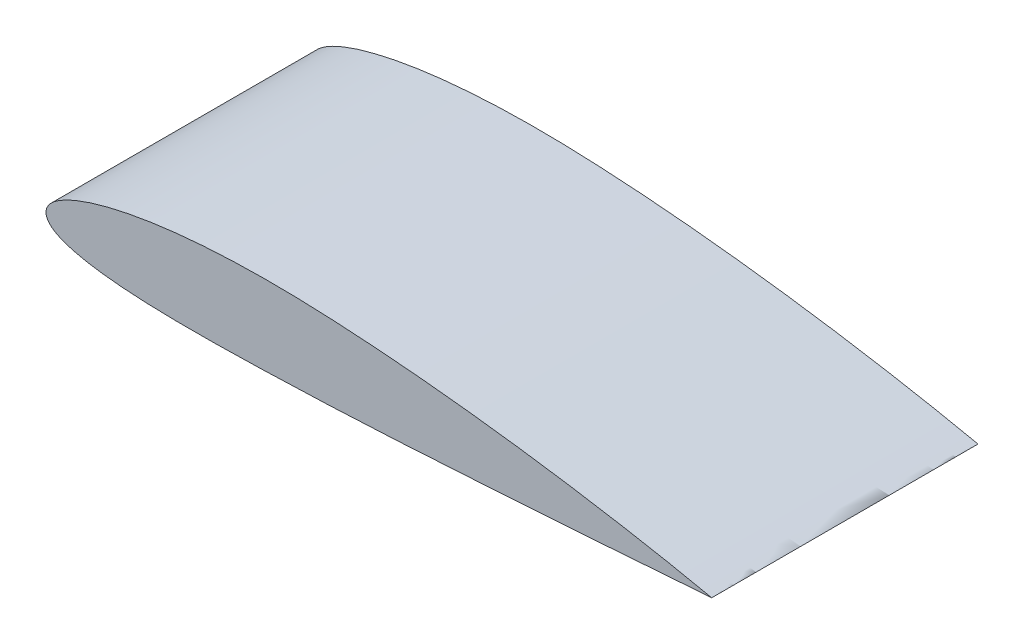
SolidWorks part; units mm, degrees
ref_plane "Front Plane"
ref_plane "Top Plane" through (0, 0, 0) normal (0, 1, 0) x (1, 0, 0)
ref_plane "Right Plane" through (0, 0, 0) normal (1, 0, 0) x (0, 0, -1)
curve "Curve2"
  spline degree 3 poles (749.6002, -0.0183, 0) (750.0992, -0.0066, 0) (749.6062, 0.0712, 0) (749.2018, 0.1788, 0) (748.204, 0.3795, 0) (746.9606, 0.6495, 0) (745.3027, 0.9992, 0) (743.302, 1.423, 0) (740.9341, 1.9213, 0) (738.2104, 2.492, 0) (735.1303, 3.1336, 0) (731.6977, 3.8441, 0) (727.9155, 4.6215, 0) (723.7872, 5.4635, 0) (719.3167, 6.3677, 0) (714.5081, 7.3314, 0) (709.366, 8.352, 0) (703.8952, 9.4265, 0) (698.1007, 10.5521, 0) (691.988, 11.7256, 0) (685.563, 12.9439, 0) (678.8316, 14.2037, 0) (671.8002, 15.5017, 0) (664.4756, 16.8346, 0) (656.8646, 18.1989, 0) (648.9745, 19.5912, 0) (640.8129, 21.008, 0) (632.3875, 22.4457, 0) (623.7065, 23.9009, 0) (614.7782, 25.3701, 0) (605.6111, 26.8497, 0) (596.2141, 28.3363, 0) (586.5964, 29.8262, 0) (576.7671, 31.316, 0) (566.7359, 32.8022, 0) (556.5125, 34.2813, 0) (546.1069, 35.7499, 0) (535.5292, 37.2046, 0) (524.7898, 38.6418, 0) (513.8991, 40.0583, 0) (502.8679, 41.4506, 0) (491.707, 42.8155, 0) (480.4274, 44.1495, 0) (469.0403, 45.4494, 0) (457.5568, 46.7119, 0) (445.9883, 47.9338, 0) (434.3464, 49.1119, 0) (422.6425, 50.2431, 0) (410.8883, 51.3242, 0) (399.0956, 52.3523, 0) (387.2762, 53.3242, 0) (375.4418, 54.2373, 0) (363.6043, 55.0885, 0) (351.7755, 55.8752, 0) (339.9675, 56.5947, 0) (328.1921, 57.2446, 0) (316.4612, 57.8222, 0) (304.7683, 58.3269, 0) (293.1124, 58.7536, 0) (281.5044, 59.0737, 0) (269.9749, 59.2908, 0) (258.5487, 59.4022, 0) (247.2379, 59.4077, 0) (236.0543, 59.3068, 0) (225.0098, 59.0996, 0) (214.1161, 58.7862, 0) (203.3848, 58.3674, 0) (192.8272, 57.8441, 0) (182.4546, 57.2175, 0) (172.2778, 56.4892, 0) (162.3077, 55.6611, 0) (152.5548, 54.7354, 0) (143.0294, 53.7146, 0) (133.7414, 52.6014, 0) (124.7005, 51.3989, 0) (115.9163, 50.1105, 0) (107.3977, 48.7396, 0) (99.1536, 47.2902, 0) (91.1924, 45.7662, 0) (83.5221, 44.1717, 0) (76.1506, 42.5112, 0) (69.0852, 40.7891, 0) (62.3329, 39.0099, 0) (55.9002, 37.1784, 0) (49.7935, 35.2991, 0) (44.0185, 33.3768, 0) (38.5806, 31.4161, 0) (33.4849, 29.4217, 0) (28.7359, 27.398, 0) (24.3378, 25.3495, 0) (20.2944, 23.2803, 0) (16.6088, 21.1944, 0) (13.2841, 19.0955, 0) (10.3224, 16.9868, 0) (7.7258, 14.8713, 0) (5.4959, 12.7512, 0) (3.634, 10.6277, 0) (2.1419, 8.5017, 0) (1.022, 6.3729, 0) (0.2783, 4.2417, 0) (-0.0843, 2.1103, 0) (-0.0622, -0.0062, 0) (0.3352, -2.0851, 0) (1.1109, -4.1024, 0) (2.257, -6.0449, 0) (3.7669, -7.9123, 0) (5.6355, -9.7063, 0) (7.8594, -11.4286, 0) (10.4356, -13.0806, 0) (13.3615, -14.6629, 0) (16.6342, -16.1757, 0) (20.2506, -17.6189, 0) (24.2069, -18.9922, 0) (28.499, -20.2953, 0) (33.1227, -21.5276, 0) (38.0731, -22.6889, 0) (43.3451, -23.7788, 0) (48.9333, -24.7972, 0) (54.832, -25.744, 0) (61.0352, -26.6192, 0) (67.5369, -27.423, 0) (74.3304, -28.1556, 0) (81.4091, -28.8177, 0) (88.7662, -29.4098, 0) (96.3944, -29.9328, 0) (104.2864, -30.3876, 0) (112.4348, -30.7756, 0) (120.8318, -31.098, 0) (129.4695, -31.3566, 0) (138.3398, -31.553, 0) (147.4345, -31.6892, 0) (156.7452, -31.7674, 0) (166.2632, -31.79, 0) (175.98, -31.7594, 0) (185.8864, -31.6782, 0) (195.9736, -31.5494, 0) (206.2322, -31.3757, 0) (216.653, -31.1602, 0) (227.2264, -30.9061, 0) (237.9428, -30.6166, 0) (248.7924, -30.2949, 0) (259.7654, -29.9444, 0) (270.8516, -29.5683, 0) (282.041, -29.1703, 0) (293.3358, -28.7518, 0) (304.7441, -28.3213, 0) (316.2539, -27.8553, 0) (327.8413, -27.354, 0) (339.477, -26.8216, 0) (351.1497, -26.2606, 0) (362.8482, -25.6738, 0) (374.5611, -25.0637, 0) (386.277, -24.4329, 0) (397.9847, -23.7839, 0) (409.6726, -23.1191, 0) (421.3295, -22.4407, 0) (432.9439, -21.7512, 0) (444.5044, -21.0525, 0) (455.9998, -20.3466, 0) (467.4187, -19.6356, 0) (478.75, -18.9211, 0) (489.9824, -18.2049, 0) (501.1048, -17.4886, 0) (512.1063, -16.7737, 0) (522.976, -16.0616, 0) (533.703, -15.3535, 0) (544.2767, -14.6508, 0) (554.6866, -13.9546, 0) (564.9222, -13.2658, 0) (574.9734, -12.5856, 0) (584.8301, -11.9149, 0) (594.4823, -11.2546, 0) (603.9204, -10.6056, 0) (613.1349, -9.9687, 0) (622.1165, -9.3446, 0) (630.8561, -8.7342, 0) (639.3449, -8.1383, 0) (647.5742, -7.5575, 0) (655.5356, -6.9926, 0) (663.2211, -6.4444, 0) (670.6228, -5.9136, 0) (677.7332, -5.4009, 0) (684.545, -4.907, 0) (691.0511, -4.4328, 0) (697.2448, -3.9789, 0) (703.1199, -3.5461, 0) (708.6702, -3.135, 0) (713.8899, -2.7465, 0) (718.7737, -2.3812, 0) (723.3165, -2.0397, 0) (727.5136, -1.7229, 0) (731.3606, -1.4312, 0) (734.8534, -1.1653, 0) (737.9886, -0.9258, 0) (740.7621, -0.7131, 0) (743.1739, -0.5279, 0) (745.2124, -0.37, 0) (746.9016, -0.2416, 0) (748.1697, -0.1382, 0) (749.1851, -0.0714, 0) (749.6002, -0.0183, 0) (750.0992, -0.0066, 0) (749.6062, 0.0712, 0) knots -0.001101 -0.000489 -0.000122 0 0.000122 0.000489 0.001101 0.001956 0.003053 0.004393 0.005972 0.007791 0.009846 0.012136 0.014659 0.017411 0.020391 0.023595 0.027019 0.030662 0.034518 0.038584 0.042856 0.04733 0.052001 0.056865 0.061917 0.067151 0.072562 0.078146 0.083896 0.089808 0.095874 0.102089 0.108447 0.114942 0.121567 0.128315 0.13518 0.142156 0.149234 0.156409 0.163672 0.171018 0.178438 0.185926 0.193473 0.201072 0.208717 0.216398 0.224109 0.231843 0.23959 0.247344 0.255098 0.262842 0.270571 0.278275 0.285948 0.293582 0.301205 0.308799 0.316333 0.323797 0.331186 0.338493 0.345709 0.352828 0.359844 0.36675 0.373538 0.380203 0.386739 0.393138 0.399397 0.405507 0.411465 0.417265 0.422901 0.428369 0.433664 0.438782 0.443718 0.448468 0.453029 0.457397 0.461571 0.465546 0.469321 0.472895 0.476266 0.479433 0.482399 0.485162 0.487728 0.490099 0.492281 0.494284 0.49612 0.497805 0.499362 0.500818 0.502209 0.503576 0.504943 0.506334 0.507789 0.509344 0.511024 0.512853 0.514846 0.517014 0.519365 0.521906 0.524639 0.527568 0.530692 0.534013 0.537529 0.541238 0.545141 0.549233 0.553512 0.557975 0.562619 0.567441 0.572435 0.577599 0.582928 0.588418 0.594063 0.599859 0.605801 0.611883 0.618101 0.624449 0.63092 0.63751 0.644213 0.651022 0.657931 0.664935 0.672025 0.679197 0.686444 0.693758 0.701134 0.708588 0.716125 0.723702 0.731312 0.738946 0.746598 0.75426 0.761925 0.769585 0.777233 0.784861 0.792462 0.800028 0.807552 0.815027 0.822444 0.829797 0.837078 0.84428 0.851397 0.85842 0.865343 0.872158 0.87886 0.885442 0.891896 0.898216 0.904397 0.910431 0.916313 0.922036 0.927595 0.932985 0.938199 0.943233 0.948081 0.952738 0.9572 0.961462 0.965519 0.969367 0.973003 0.976423 0.979622 0.982598 0.985348 0.987869 0.990157 0.992211 0.994029 0.995608 0.996947 0.998045 0.998899 0.999511 0.999878 1 1.000122 1.000489 1.001101 periodic
sketch "Sketch3" plane through (0, 0, 0) normal (0, 0, 1) x (1, 0, 0)
  spline S0 degree 3 poles (749.6002, -0.0183) (750.0992, -0.0066) (749.6062, 0.0712) (749.2018, 0.1788) (748.204, 0.3795) (746.9606, 0.6495) (745.3027, 0.9992) (743.302, 1.423) (740.9341, 1.9213) (738.2104, 2.492) (735.1303, 3.1336) (731.6977, 3.8441) (727.9155, 4.6215) (723.7872, 5.4635) (719.3167, 6.3677) (714.5081, 7.3314) (709.366, 8.352) (703.8952, 9.4265) (698.1007, 10.5521) (691.988, 11.7256) (685.563, 12.9439) (678.8316, 14.2037) (671.8002, 15.5017) (664.4756, 16.8346) (656.8646, 18.1989) (648.9745, 19.5912) (640.8129, 21.008) (632.3875, 22.4457) (623.7065, 23.9009) (614.7782, 25.3701) (605.6111, 26.8497) (596.2141, 28.3363) (586.5964, 29.8262) (576.7671, 31.316) (566.7359, 32.8022) (556.5125, 34.2813) (546.1069, 35.7499) (535.5292, 37.2046) (524.7898, 38.6418) (513.8991, 40.0583) (502.8679, 41.4506) (491.707, 42.8155) (480.4274, 44.1495) (469.0403, 45.4494) (457.5568, 46.7119) (445.9883, 47.9338) (434.3464, 49.1119) (422.6425, 50.2431) (410.8883, 51.3242) (399.0956, 52.3523) (387.2762, 53.3242) (375.4418, 54.2373) (363.6043, 55.0885) (351.7755, 55.8752) (339.9675, 56.5947) (328.1921, 57.2446) (316.4612, 57.8222) (304.7683, 58.3269) (293.1124, 58.7536) (281.5044, 59.0737) (269.9749, 59.2908) (258.5487, 59.4022) (247.2379, 59.4077) (236.0543, 59.3068) (225.0098, 59.0996) (214.1161, 58.7862) (203.3848, 58.3674) (192.8272, 57.8441) (182.4546, 57.2175) (172.2778, 56.4892) (162.3077, 55.6611) (152.5548, 54.7354) (143.0294, 53.7146) (133.7414, 52.6014) (124.7005, 51.3989) (115.9163, 50.1105) (107.3977, 48.7396) (99.1536, 47.2902) (91.1924, 45.7662) (83.5221, 44.1717) (76.1506, 42.5112) (69.0852, 40.7891) (62.3329, 39.0099) (55.9002, 37.1784) (49.7935, 35.2991) (44.0185, 33.3768) (38.5806, 31.4161) (33.4849, 29.4217) (28.7359, 27.398) (24.3378, 25.3495) (20.2944, 23.2803) (16.6088, 21.1944) (13.2841, 19.0955) (10.3224, 16.9868) (7.7258, 14.8713) (5.4959, 12.7512) (3.634, 10.6277) (2.1419, 8.5017) (1.022, 6.3729) (0.2783, 4.2417) (-0.0843, 2.1103) (-0.0622, -0.0062) (0.3352, -2.0851) (1.1109, -4.1024) (2.257, -6.0449) (3.7669, -7.9123) (5.6355, -9.7063) (7.8594, -11.4286) (10.4356, -13.0806) (13.3615, -14.6629) (16.6342, -16.1757) (20.2506, -17.6189) (24.2069, -18.9922) (28.499, -20.2953) (33.1227, -21.5276) (38.0731, -22.6889) (43.3451, -23.7788) (48.9333, -24.7972) (54.832, -25.744) (61.0352, -26.6192) (67.5369, -27.423) (74.3304, -28.1556) (81.4091, -28.8177) (88.7662, -29.4098) (96.3944, -29.9328) (104.2864, -30.3876) (112.4348, -30.7756) (120.8318, -31.098) (129.4695, -31.3566) (138.3398, -31.553) (147.4345, -31.6892) (156.7452, -31.7674) (166.2632, -31.79) (175.98, -31.7594) (185.8864, -31.6782) (195.9736, -31.5494) (206.2322, -31.3757) (216.653, -31.1602) (227.2264, -30.9061) (237.9428, -30.6166) (248.7924, -30.2949) (259.7654, -29.9444) (270.8516, -29.5683) (282.041, -29.1703) (293.3358, -28.7518) (304.7441, -28.3213) (316.2539, -27.8553) (327.8413, -27.354) (339.477, -26.8216) (351.1497, -26.2606) (362.8482, -25.6738) (374.5611, -25.0637) (386.277, -24.4329) (397.9847, -23.7839) (409.6726, -23.1191) (421.3295, -22.4407) (432.9439, -21.7512) (444.5044, -21.0525) (455.9998, -20.3466) (467.4187, -19.6356) (478.75, -18.9211) (489.9824, -18.2049) (501.1048, -17.4886) (512.1063, -16.7737) (522.976, -16.0616) (533.703, -15.3535) (544.2767, -14.6508) (554.6866, -13.9546) (564.9222, -13.2658) (574.9734, -12.5856) (584.8301, -11.9149) (594.4823, -11.2546) (603.9204, -10.6056) (613.1349, -9.9687) (622.1165, -9.3446) (630.8561, -8.7342) (639.3449, -8.1383) (647.5742, -7.5575) (655.5356, -6.9926) (663.2211, -6.4444) (670.6228, -5.9136) (677.7332, -5.4009) (684.545, -4.907) (691.0511, -4.4328) (697.2448, -3.9789) (703.1199, -3.5461) (708.6702, -3.135) (713.8899, -2.7465) (718.7737, -2.3812) (723.3165, -2.0397) (727.5136, -1.7229) (731.3606, -1.4312) (734.8534, -1.1653) (737.9886, -0.9258) (740.7621, -0.7131) (743.1739, -0.5279) (745.2124, -0.37) (746.9016, -0.2416) (748.1697, -0.1382) (749.1851, -0.0714) (749.6002, -0.0183) (750.0992, -0.0066) (749.6062, 0.0712) knots -0.001101 -0.000489 -0.000122 0 0.000122 0.000489 0.001101 0.001956 0.003053 0.004393 0.005972 0.007791 0.009846 0.012136 0.014659 0.017411 0.020391 0.023595 0.027019 0.030662 0.034518 0.038584 0.042856 0.04733 0.052001 0.056865 0.061917 0.067151 0.072562 0.078146 0.083896 0.089808 0.095874 0.102089 0.108447 0.114942 0.121567 0.128315 0.13518 0.142156 0.149234 0.156409 0.163672 0.171018 0.178438 0.185926 0.193473 0.201072 0.208717 0.216398 0.224109 0.231843 0.23959 0.247344 0.255098 0.262842 0.270571 0.278275 0.285948 0.293582 0.301205 0.308799 0.316333 0.323797 0.331186 0.338493 0.345709 0.352828 0.359844 0.36675 0.373538 0.380203 0.386739 0.393138 0.399397 0.405507 0.411465 0.417265 0.422901 0.428369 0.433664 0.438782 0.443718 0.448468 0.453029 0.457397 0.461571 0.465546 0.469321 0.472895 0.476266 0.479433 0.482399 0.485162 0.487728 0.490099 0.492281 0.494284 0.49612 0.497805 0.499362 0.500818 0.502209 0.503576 0.504943 0.506334 0.507789 0.509344 0.511024 0.512853 0.514846 0.517014 0.519365 0.521906 0.524639 0.527568 0.530692 0.534013 0.537529 0.541238 0.545141 0.549233 0.553512 0.557975 0.562619 0.567441 0.572435 0.577599 0.582928 0.588418 0.594063 0.599859 0.605801 0.611883 0.618101 0.624449 0.63092 0.63751 0.644213 0.651022 0.657931 0.664935 0.672025 0.679197 0.686444 0.693758 0.701134 0.708588 0.716125 0.723702 0.731312 0.738946 0.746598 0.75426 0.761925 0.769585 0.777233 0.784861 0.792462 0.800028 0.807552 0.815027 0.822444 0.829797 0.837078 0.84428 0.851397 0.85842 0.865343 0.872158 0.87886 0.885442 0.891896 0.898216 0.904397 0.910431 0.916313 0.922036 0.927595 0.932985 0.938199 0.943233 0.948081 0.952738 0.9572 0.961462 0.965519 0.969367 0.973003 0.976423 0.979622 0.982598 0.985348 0.987869 0.990157 0.992211 0.994029 0.995608 0.996947 0.998045 0.998899 0.999511 0.999878 1 1.000122 1.000489 1.001101 only from (750, 0) to (750, 0) construction
  spline S1 degree 3 poles (749.6002, -0.0183) (750.0992, -0.0066) (749.6062, 0.0712) (749.2018, 0.1788) (748.204, 0.3795) (746.9606, 0.6495) (745.3027, 0.9992) (743.302, 1.423) (740.9341, 1.9213) (738.2104, 2.492) (735.1303, 3.1336) (731.6977, 3.8441) (727.9155, 4.6215) (723.7872, 5.4635) (719.3167, 6.3677) (714.5081, 7.3314) (709.366, 8.352) (703.8952, 9.4265) (698.1007, 10.5521) (691.988, 11.7256) (685.563, 12.9439) (678.8316, 14.2037) (671.8002, 15.5017) (664.4756, 16.8346) (656.8646, 18.1989) (648.9745, 19.5912) (640.8129, 21.008) (632.3875, 22.4457) (623.7065, 23.9009) (614.7782, 25.3701) (605.6111, 26.8497) (596.2141, 28.3363) (586.5964, 29.8262) (576.7671, 31.316) (566.7359, 32.8022) (556.5125, 34.2813) (546.1069, 35.7499) (535.5292, 37.2046) (524.7898, 38.6418) (513.8991, 40.0583) (502.8679, 41.4506) (491.707, 42.8155) (480.4274, 44.1495) (469.0403, 45.4494) (457.5568, 46.7119) (445.9883, 47.9338) (434.3464, 49.1119) (422.6425, 50.2431) (410.8883, 51.3242) (399.0956, 52.3523) (387.2762, 53.3242) (375.4418, 54.2373) (363.6043, 55.0885) (351.7755, 55.8752) (339.9675, 56.5947) (328.1921, 57.2446) (316.4612, 57.8222) (304.7683, 58.3269) (293.1124, 58.7536) (281.5044, 59.0737) (269.9749, 59.2908) (258.5487, 59.4022) (247.2379, 59.4077) (236.0543, 59.3068) (225.0098, 59.0996) (214.1161, 58.7862) (203.3848, 58.3674) (192.8272, 57.8441) (182.4546, 57.2175) (172.2778, 56.4892) (162.3077, 55.6611) (152.5548, 54.7354) (143.0294, 53.7146) (133.7414, 52.6014) (124.7005, 51.3989) (115.9163, 50.1105) (107.3977, 48.7396) (99.1536, 47.2902) (91.1924, 45.7662) (83.5221, 44.1717) (76.1506, 42.5112) (69.0852, 40.7891) (62.3329, 39.0099) (55.9002, 37.1784) (49.7935, 35.2991) (44.0185, 33.3768) (38.5806, 31.4161) (33.4849, 29.4217) (28.7359, 27.398) (24.3378, 25.3495) (20.2944, 23.2803) (16.6088, 21.1944) (13.2841, 19.0955) (10.3224, 16.9868) (7.7258, 14.8713) (5.4959, 12.7512) (3.634, 10.6277) (2.1419, 8.5017) (1.022, 6.3729) (0.2783, 4.2417) (-0.0843, 2.1103) (-0.0622, -0.0062) (0.3352, -2.0851) (1.1109, -4.1024) (2.257, -6.0449) (3.7669, -7.9123) (5.6355, -9.7063) (7.8594, -11.4286) (10.4356, -13.0806) (13.3615, -14.6629) (16.6342, -16.1757) (20.2506, -17.6189) (24.2069, -18.9922) (28.499, -20.2953) (33.1227, -21.5276) (38.0731, -22.6889) (43.3451, -23.7788) (48.9333, -24.7972) (54.832, -25.744) (61.0352, -26.6192) (67.5369, -27.423) (74.3304, -28.1556) (81.4091, -28.8177) (88.7662, -29.4098) (96.3944, -29.9328) (104.2864, -30.3876) (112.4348, -30.7756) (120.8318, -31.098) (129.4695, -31.3566) (138.3398, -31.553) (147.4345, -31.6892) (156.7452, -31.7674) (166.2632, -31.79) (175.98, -31.7594) (185.8864, -31.6782) (195.9736, -31.5494) (206.2322, -31.3757) (216.653, -31.1602) (227.2264, -30.9061) (237.9428, -30.6166) (248.7924, -30.2949) (259.7654, -29.9444) (270.8516, -29.5683) (282.041, -29.1703) (293.3358, -28.7518) (304.7441, -28.3213) (316.2539, -27.8553) (327.8413, -27.354) (339.477, -26.8216) (351.1497, -26.2606) (362.8482, -25.6738) (374.5611, -25.0637) (386.277, -24.4329) (397.9847, -23.7839) (409.6726, -23.1191) (421.3295, -22.4407) (432.9439, -21.7512) (444.5044, -21.0525) (455.9998, -20.3466) (467.4187, -19.6356) (478.75, -18.9211) (489.9824, -18.2049) (501.1048, -17.4886) (512.1063, -16.7737) (522.976, -16.0616) (533.703, -15.3535) (544.2767, -14.6508) (554.6866, -13.9546) (564.9222, -13.2658) (574.9734, -12.5856) (584.8301, -11.9149) (594.4823, -11.2546) (603.9204, -10.6056) (613.1349, -9.9687) (622.1165, -9.3446) (630.8561, -8.7342) (639.3449, -8.1383) (647.5742, -7.5575) (655.5356, -6.9926) (663.2211, -6.4444) (670.6228, -5.9136) (677.7332, -5.4009) (684.545, -4.907) (691.0511, -4.4328) (697.2448, -3.9789) (703.1199, -3.5461) (708.6702, -3.135) (713.8899, -2.7465) (718.7737, -2.3812) (723.3165, -2.0397) (727.5136, -1.7229) (731.3606, -1.4312) (734.8534, -1.1653) (737.9886, -0.9258) (740.7621, -0.7131) (743.1739, -0.5279) (745.2124, -0.37) (746.9016, -0.2416) (748.1697, -0.1382) (749.1851, -0.0714) (749.6002, -0.0183) (750.0992, -0.0066) (749.6062, 0.0712) knots -0.001101 -0.000489 -0.000122 0 0.000122 0.000489 0.001101 0.001956 0.003053 0.004393 0.005972 0.007791 0.009846 0.012136 0.014659 0.017411 0.020391 0.023595 0.027019 0.030662 0.034518 0.038584 0.042856 0.04733 0.052001 0.056865 0.061917 0.067151 0.072562 0.078146 0.083896 0.089808 0.095874 0.102089 0.108447 0.114942 0.121567 0.128315 0.13518 0.142156 0.149234 0.156409 0.163672 0.171018 0.178438 0.185926 0.193473 0.201072 0.208717 0.216398 0.224109 0.231843 0.23959 0.247344 0.255098 0.262842 0.270571 0.278275 0.285948 0.293582 0.301205 0.308799 0.316333 0.323797 0.331186 0.338493 0.345709 0.352828 0.359844 0.36675 0.373538 0.380203 0.386739 0.393138 0.399397 0.405507 0.411465 0.417265 0.422901 0.428369 0.433664 0.438782 0.443718 0.448468 0.453029 0.457397 0.461571 0.465546 0.469321 0.472895 0.476266 0.479433 0.482399 0.485162 0.487728 0.490099 0.492281 0.494284 0.49612 0.497805 0.499362 0.500818 0.502209 0.503576 0.504943 0.506334 0.507789 0.509344 0.511024 0.512853 0.514846 0.517014 0.519365 0.521906 0.524639 0.527568 0.530692 0.534013 0.537529 0.541238 0.545141 0.549233 0.553512 0.557975 0.562619 0.567441 0.572435 0.577599 0.582928 0.588418 0.594063 0.599859 0.605801 0.611883 0.618101 0.624449 0.63092 0.63751 0.644213 0.651022 0.657931 0.664935 0.672025 0.679197 0.686444 0.693758 0.701134 0.708588 0.716125 0.723702 0.731312 0.738946 0.746598 0.75426 0.761925 0.769585 0.777233 0.784861 0.792462 0.800028 0.807552 0.815027 0.822444 0.829797 0.837078 0.84428 0.851397 0.85842 0.865343 0.872158 0.87886 0.885442 0.891896 0.898216 0.904397 0.910431 0.916313 0.922036 0.927595 0.932985 0.938199 0.943233 0.948081 0.952738 0.9572 0.961462 0.965519 0.969367 0.973003 0.976423 0.979622 0.982598 0.985348 0.987869 0.990157 0.992211 0.994029 0.995608 0.996947 0.998045 0.998899 0.999511 0.999878 1 1.000122 1.000489 1.001101 only from (750, 0) to (750, 0)
extrude "Boss-Extrude1" add sketch "Sketch3" along normal blind 300
equation "\"AoA\"= - 4"
